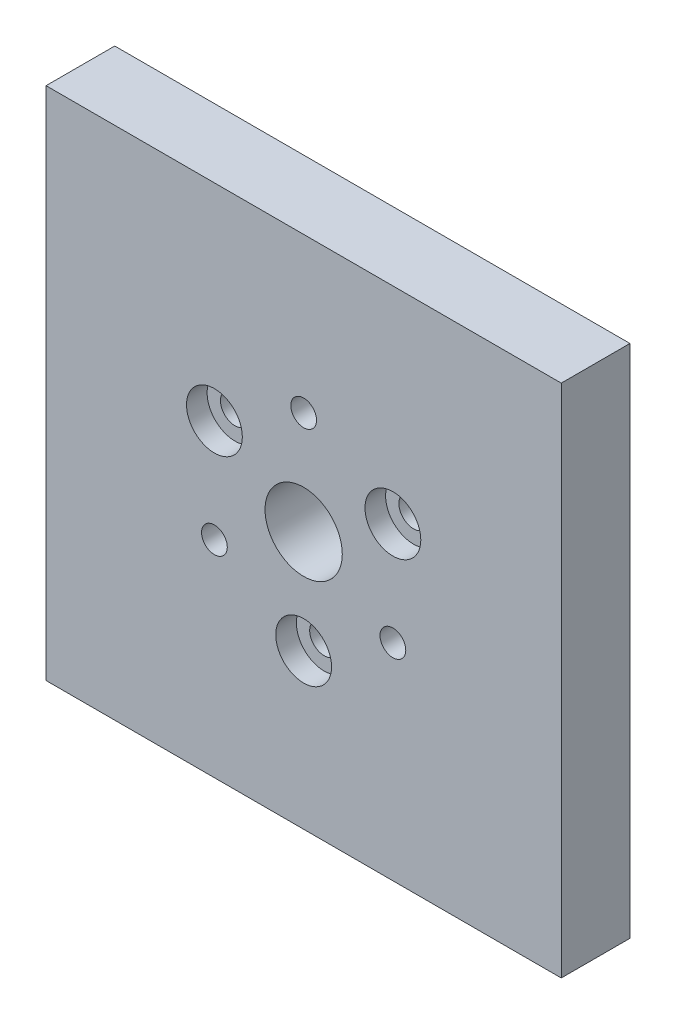
SolidWorks part; units mm, degrees
material "6061-T6 (SS)"
ref_plane "Front Plane" through (0, 0, 0) normal (0, 0, 1) x (1, 0, 0)
ref_plane "Top Plane" through (0, 0, 0) normal (0, 1, 0) x (1, 0, 0)
ref_plane "Right Plane" through (0, 0, 0) normal (1, 0, 0) x (0, 0, -1)
sketch "Sketch1" plane through (0, 0, 0) normal (0, 0, 1) x (1, 0, 0)
  line L1 (0, 0) -> (60, 0)
  line L2 (0, 0) -> (0, 60)
  line L3 (0, 60) -> (60, 60)
  line L4 (60, 0) -> (60, 60)
  dimension "D1" = 60
  dimension "D2" = 60
extrude "Boss-Extrude1" add sketch "Sketch1" along normal blind 8
sketch "Sketch2" plane through (0, 0, 8) normal (0, 0, 1) x (1, 0, 0)
  line L0 (0, 60) -> (60, 0) construction
  line L1 (60, 0) -> (60, 60) construction
  line L2 (60, 60) -> (0, 0) construction
  point P12 (30, 30)
hole_wizard "M8 Clearance Hole1" positions "Sketch2" profile "Sketch3" hole size "M8" standard "DIN" end condition through all
sketch "Sketch3" plane through (30, 30, 8) normal (1, 0, 0) x (0, -1, 0)
  line L0 (0, 0) -> (0, 8)
  line L1 (0, 8) -> (4.5, 8)
  line L2 (4.5, 8) -> (4.5, 0)
  line L5 (4.5, 0) -> (0, 0)
  line L11 (0, -6.35) -> (0, 107.95) construction
  dimension "Thru Hole Dia." = 9
  dimension "Thru Hole Depth" = 8
sketch "Sketch4" plane through (0, 0, 8) normal (0, 0, 1) x (1, 0, 0)
  circle A0 centre (30, 30) radius 12 construction
  point P5 (30, 42)
  point P12 (40.3923, 24)
  point P13 (19.6077, 24)
  dimension "D1" = 24
  dimension "D2" = 3
hole_wizard "Ø3.0mm Dowel Hole1" positions "Sketch4" profile "Sketch5" hole size "Ø3.0" standard "DIN" end condition through all
sketch "Sketch5" plane through (19.6077, 24, 8) normal (1, 0, 0) x (0, -1, 0)
  line L0 (0, 0) -> (0, 8)
  line L1 (0, 8) -> (1.5, 8)
  line L2 (1.5, 8) -> (1.5, 0)
  line L5 (1.5, 0) -> (0, 0)
  line L11 (0, -6.35) -> (0, 107.95) construction
  dimension "Thru Hole Dia." = 3
  dimension "Thru Hole Depth" = 8
sketch "Sketch8" plane through (0, 0, 8) normal (0, 0, 1) x (1, 0, 0)
  circle A0 centre (30, 30) radius 12
  point P6 (30, 18)
  point P13 (19.6077, 36)
  point P14 (40.3923, 36)
  dimension "D1" = 3
hole_wizard "CBORE for M3 Hex Socket Thin Head Cap Screw1" positions "Sketch8" profile "Sketch9" counterbore size "M3" standard "DIN" end condition through all
sketch "Sketch9" plane through (40.3923, 36, 8) normal (1, 0, 0) x (0, -1, 0)
  line L0 (0, 0) -> (0, 8)
  line L1 (0, 8) -> (1.7, 8)
  line L3 (1.7, 8) -> (1.7, 2.4)
  line L4 (1.7, 2.4) -> (3.25, 2.4)
  line L5 (3.25, 2.4) -> (3.25, 0)
  line L7 (3.25, 0) -> (0, 0)
  line L11 (0, -6.35) -> (0, 107.95) construction
  dimension "Thru Hole Dia." = 3.4
  dimension "Thru Hole Depth" = 8
  dimension "C'Bore Dia." = 6.5
  dimension "C'Bore Depth" = 2.4
